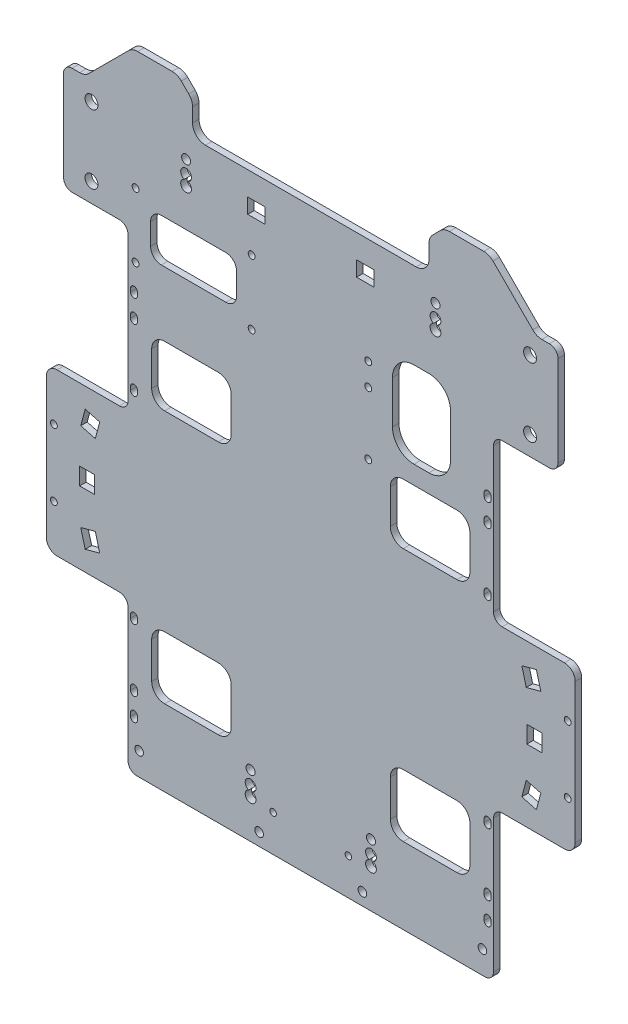
SolidWorks part; units mm, degrees
ref_plane "前视基准面" through (0, 0, 0) normal (0, 0, 1) x (1, 0, 0)
ref_plane "上视基准面" through (0, 0, 0) normal (0, 1, 0) x (1, 0, 0)
ref_plane "右视基准面" through (0, 0, 0) normal (1, 0, 0) x (0, 0, -1)
sketch "草图1" plane through (0, 0, 0) normal (0, 0, 1) x (1, 0, 0)
  line L0 (-31.6443, 41.9463) -> (-31.6443, -8.1198) construction
  line L1 (-146.6443, 41.9463) -> (83.3557, 41.9463)
  line L2 (-146.6443, 41.9463) -> (-146.6443, -8.0537)
  line L3 (-116.6443, -228.0537) -> (53.3557, -228.0537)
  line L4 (83.3557, 41.9463) -> (83.3557, -8.0537)
  line L5 (83.3557, -8.0537) -> (53.3557, -8.0537)
  line L6 (33.3557, 1.9463) -> (6.3557, 1.9463)
  line L7 (83.3557, -83.0537) -> (53.3557, -83.0537)
  line L8 (53.3557, -8.0537) -> (53.3557, -83.0537)
  line L9 (83.3557, -158.0537) -> (53.3557, -158.0537)
  line L10 (33.3557, -38.0537) -> (6.3557, -38.0537)
  line L11 (6.3557, 1.9463) -> (6.3557, -38.0537)
  line L12 (53.3557, -158.0537) -> (53.3557, -228.0537)
  line L14 (-116.6443, -158.0537) -> (-116.6443, -228.0537)
  line L15 (-146.6443, -158.0537) -> (-116.6443, -158.0537)
  line L16 (-146.6443, -83.0537) -> (-116.6443, -83.0537)
  line L17 (-116.6443, -8.0537) -> (-116.6443, -83.0537)
  line L18 (-146.6443, -8.0537) -> (-116.6443, -8.0537)
  line L19 (-146.6443, -83.0537) -> (-146.6443, -158.0537)
  line L20 (33.3557, 1.9463) -> (33.3557, -38.0537)
  line L22 (83.3557, -83.0537) -> (83.3557, -158.0537)
  circle A0 centre (-4.8943, -7.2137) radius 1.6
  circle A1 centre (-4.8943, -17.7137) radius 1.6
  circle A2 centre (-4.8943, -46.7137) radius 1.6
  dimension "D10" = 3.2
  dimension "D12" = 49.16
  dimension "D13" = 10.5
  dimension "D14" = 29
  dimension "D15" = 3.2
  dimension "D16" = 3.2
  dimension "D1" = 230
  dimension "D2" = 50
  dimension "D3" = 50
  dimension "D4" = 30
  dimension "D5" = 30
  dimension "D6" = 75
  dimension "D7" = 70
  dimension "D8" = 75
  dimension "D9" = 27
  dimension "D11" = 11.25
extrude "凸台-拉伸1" add sketch "草图1" along normal blind 3
sketch "草图2" plane through (0, 0, 3) normal (0, 0, 1) x (1, 0, 0)
  line L0 (83.3557, -158.0537) -> (83.3557, -83.0537) construction
  line L1 (-116.6443, -228.0537) -> (53.3557, -228.0537) construction
  circle A0 centre (25.3557, -107.0537) radius 6
  circle A1 centre (31.8472, -88.1365) radius 6
  circle A2 centre (25.3557, -68.1365) radius 6
  dimension "D4" = 12
  dimension "D5" = 12
  dimension "D6" = 12
  dimension "D1" = 58
  dimension "D2" = 121
  dimension "D3" = 20
  dimension "D7" = 20
sketch "草图3" plane through (0, 0, 3) normal (0, 0, 1) x (1, 0, 0)
  line L0 (49.0057, -72.5537) -> (49.0057, -74.1537)
  line L1 (53.3557, -228.0537) -> (53.3557, -158.0537) construction
  line L2 (52.2057, -72.5537) -> (52.2057, -74.1537)
  line L3 (53.3557, -83.0537) -> (53.3557, -8.0537) construction
  line L4 (-31.6443, -208.0537) -> (-31.6443, 49791.9463) construction
  line L5 (-116.6443, -228.0537) -> (53.3557, -228.0537) construction
  line L6 (83.3557, 41.9463) -> (-146.6443, 41.9463) construction
  line L7 (49.0057, -43.5537) -> (49.0057, -45.1537)
  line L8 (52.2057, -43.5537) -> (52.2057, -45.1537)
  line L9 (49.0057, -33.0537) -> (49.0057, -34.6537)
  line L10 (52.2057, -33.0537) -> (52.2057, -34.6537)
  line L11 (49.0057, -164.4537) -> (49.0057, -166.0537)
  line L12 (52.2057, -164.4537) -> (52.2057, -166.0537)
  line L13 (49.0057, -193.4537) -> (49.0057, -195.0537)
  line L14 (52.2057, -193.4537) -> (52.2057, -195.0537)
  line L15 (49.0057, -203.9537) -> (49.0057, -205.5537)
  line L16 (52.2057, -203.9537) -> (52.2057, -205.5537)
  line L17 (-115.4943, -33.0537) -> (-115.4943, -34.6537)
  line L18 (-112.2943, -33.0537) -> (-112.2943, -34.6537)
  line L19 (-115.4943, -43.5537) -> (-115.4943, -45.1537)
  line L20 (-112.2943, -43.5537) -> (-112.2943, -45.1537)
  line L21 (-115.4943, -72.5537) -> (-115.4943, -74.1537)
  line L22 (-112.2943, -72.5537) -> (-112.2943, -74.1537)
  line L23 (-115.4943, -164.4537) -> (-115.4943, -166.0537)
  line L24 (-112.2943, -164.4537) -> (-112.2943, -166.0537)
  line L25 (-115.4943, -193.4537) -> (-115.4943, -195.0537)
  line L26 (-112.2943, -193.4537) -> (-112.2943, -195.0537)
  line L27 (-115.4943, -203.9537) -> (-115.4943, -205.5537)
  line L28 (-112.2943, -203.9537) -> (-112.2943, -205.5537)
  arc A0 (49.0057, -166.0537) -> (52.2057, -166.0537) centre (50.6057, -166.0537) ccw
  arc A1 (49.0057, -195.0537) -> (52.2057, -195.0537) centre (50.6057, -195.0537) ccw
  arc A2 (49.0057, -205.5537) -> (52.2057, -205.5537) centre (50.6057, -205.5537) ccw
  arc A3 (52.2057, -72.5537) -> (49.0057, -72.5537) centre (50.6057, -72.5537) ccw
  arc A4 (52.2057, -43.5537) -> (49.0057, -43.5537) centre (50.6057, -43.5537) ccw
  arc A5 (52.2057, -33.0537) -> (49.0057, -33.0537) centre (50.6057, -33.0537) ccw
  arc A12 (49.0057, -34.6537) -> (52.2057, -34.6537) centre (50.6057, -34.6537) ccw
  arc A13 (49.0057, -45.1537) -> (52.2057, -45.1537) centre (50.6057, -45.1537) ccw
  arc A14 (49.0057, -74.1537) -> (52.2057, -74.1537) centre (50.6057, -74.1537) ccw
  arc A15 (52.2057, -203.9537) -> (49.0057, -203.9537) centre (50.6057, -203.9537) ccw
  arc A16 (52.2057, -193.4537) -> (49.0057, -193.4537) centre (50.6057, -193.4537) ccw
  arc A17 (52.2057, -164.4537) -> (49.0057, -164.4537) centre (50.6057, -164.4537) ccw
  arc A18 (-115.4943, -33.0537) -> (-112.2943, -33.0537) centre (-113.8943, -33.0537) cw
  arc A19 (-112.2943, -34.6537) -> (-115.4943, -34.6537) centre (-113.8943, -34.6537) cw
  arc A20 (-115.4943, -43.5537) -> (-112.2943, -43.5537) centre (-113.8943, -43.5537) cw
  arc A21 (-112.2943, -45.1537) -> (-115.4943, -45.1537) centre (-113.8943, -45.1537) cw
  arc A22 (-115.4943, -72.5537) -> (-112.2943, -72.5537) centre (-113.8943, -72.5537) cw
  arc A23 (-112.2943, -74.1537) -> (-115.4943, -74.1537) centre (-113.8943, -74.1537) cw
  arc A24 (-115.4943, -164.4537) -> (-112.2943, -164.4537) centre (-113.8943, -164.4537) cw
  arc A25 (-112.2943, -166.0537) -> (-115.4943, -166.0537) centre (-113.8943, -166.0537) cw
  arc A26 (-115.4943, -193.4537) -> (-112.2943, -193.4537) centre (-113.8943, -193.4537) cw
  arc A27 (-112.2943, -195.0537) -> (-115.4943, -195.0537) centre (-113.8943, -195.0537) cw
  arc A28 (-115.4943, -203.9537) -> (-112.2943, -203.9537) centre (-113.8943, -203.9537) cw
  arc A29 (-112.2943, -205.5537) -> (-115.4943, -205.5537) centre (-113.8943, -205.5537) cw
  point P24 (-31.6443, -228.0537)
  dimension "D1" = 3.2
  dimension "D2" = 3.2
  dimension "D3" = 3.2
  dimension "D10" = 3.2
  dimension "D11" = 3.2
  dimension "D12" = 3.2
  dimension "D4" = 29
  dimension "D5" = 22.5
  dimension "D6" = 2.75
  dimension "D7" = 0
  dimension "D8" = 2.75
  dimension "D9" = 10.5
  dimension "D13" = 2.75
  dimension "D14" = 2.75
  dimension "D15" = 29
  dimension "D16" = 10.5
  dimension "D17" = 75
  dimension "D18" = 2.75
extrude "切除-拉伸1" cut sketch "草图3" against normal blind 10
fillet "圆角1" radius 4 10 edges at (83.3557, 41.9463, 1.5) (83.3557, -8.0537, 1.5) (83.3557, -83.0537, 1.5) (83.3557, -158.0537, 1.5) (53.3557, -228.0537, 1.5) (-116.6443, -228.0537, 1.5) (-146.6443, -158.0537, 1.5) (-146.6443, -83.0537, 1.5) (-146.6443, -8.0537, 1.5) (-146.6443, 41.9463, 1.5)
sketch "草图4" plane through (0, 0, 3) normal (0, 0, 1) x (1, 0, 0)
  line L0 (83.3557, -120.5537) -> (-182.0134, -120.5537) construction
  line L1 (83.3557, -154.0537) -> (83.3557, -87.0537) construction
  line L2 (-31.6443, -228.0537) -> (-31.6443, 167.0976) construction
  line L3 (-112.6443, -228.0537) -> (49.3557, -228.0537) construction
  line L4 (75.8557, -116.5537) -> (75.8557, -124.5537)
  line L5 (75.8557, -124.5537) -> (68.8557, -124.5537)
  line L6 (68.8557, -124.5537) -> (68.8557, -116.5537)
  line L7 (68.8557, -116.5537) -> (75.8557, -116.5537)
  line L8 (75.3557, -100.0537) -> (73.2852, -92.3263)
  line L9 (73.2852, -92.3263) -> (66.5237, -94.138)
  line L10 (66.5237, -94.138) -> (68.5942, -101.8654)
  line L11 (68.5942, -101.8654) -> (75.3557, -100.0537)
  line L13 (79.3557, -83.0537) -> (53.3557, -83.0537) construction
  line L14 (66.5237, -146.9694) -> (68.5942, -139.242)
  line L15 (73.2852, -148.7811) -> (66.5237, -146.9694)
  line L16 (75.3557, -141.0537) -> (73.2852, -148.7811)
  line L17 (68.5942, -139.242) -> (75.3557, -141.0537)
  line L18 (-129.8123, -94.138) -> (-131.8828, -101.8654)
  line L19 (-136.5737, -92.3263) -> (-129.8123, -94.138)
  line L20 (-138.6443, -100.0537) -> (-136.5737, -92.3263)
  line L21 (-131.8828, -101.8654) -> (-138.6443, -100.0537)
  line L22 (-132.1443, -124.5537) -> (-132.1443, -116.5537)
  line L23 (-139.1443, -124.5537) -> (-132.1443, -124.5537)
  line L24 (-139.1443, -116.5537) -> (-139.1443, -124.5537)
  line L25 (-132.1443, -116.5537) -> (-139.1443, -116.5537)
  line L26 (-136.5737, -148.7811) -> (-129.8123, -146.9694)
  line L27 (-138.6443, -141.0537) -> (-136.5737, -148.7811)
  line L28 (-131.8828, -139.242) -> (-138.6443, -141.0537)
  line L29 (-129.8123, -146.9694) -> (-131.8828, -139.242)
  dimension "D1" = 4
  dimension "D2" = 8
  dimension "D3" = 7
  dimension "D4" = 14.5
  dimension "D5" = 8
  dimension "D6" = 7
  dimension "D8" = 17
  dimension "D9" = 8
  dimension "D10" = 8
extrude "切除-拉伸2" cut sketch "草图4" against normal through all
sketch "草图5" plane through (0, 0, 3) normal (0, 0, 1) x (1, 0, 0)
  line L0 (-31.6443, -291.5199) -> (-31.6443, 100.9656) construction
  line L6 (83.3557, -4.0537) -> (83.3557, 37.9463) construction
  line L7 (79.3557, 41.9463) -> (-142.6443, 41.9463) construction
  circle A0 centre (70.3557, 32.9463) radius 3
  circle A1 centre (70.3557, 0.9463) radius 3
  circle A2 centre (-133.6443, 0.9463) radius 3
  circle A3 centre (-133.6443, 32.9463) radius 3
  dimension "D8" = 6
  dimension "D9" = 6
  dimension "D10" = 9
  dimension "D11" = 13
  dimension "D12" = 13
  dimension "D13" = 32
extrude "切除-拉伸3" cut sketch "草图5" against normal through all
sketch "草图6" plane through (0, 0, 3) normal (0, 0, 1) x (1, 0, 0)
  line L1 (-116.6443, -8.0537) -> (-116.6443, -83.0537) construction
  line L2 (79.3557, 41.9463) -> (-142.6443, 41.9463) construction
  line L3 (-106.1443, -1.5537) -> (-106.1443, -11.5537)
  line L4 (-101.1443, -16.5537) -> (-71.1443, -16.5537)
  line L5 (-66.1443, -11.5537) -> (-66.1443, -1.5537)
  line L6 (-71.1443, 3.4463) -> (-101.1443, 3.4463)
  circle A2 centre (-113.1443, -21.5537) radius 1.6
  circle A3 centre (-59.1443, -21.5537) radius 1.6
  circle A4 centre (-113.1443, 8.4463) radius 1.6
  circle A5 centre (-59.1443, 8.4463) radius 1.6
  arc A6 (-106.1443, -1.5537) -> (-101.1443, 3.4463) centre (-101.1443, -1.5537) cw
  arc A7 (-71.1443, 3.4463) -> (-66.1443, -1.5537) centre (-71.1443, -1.5537) cw
  arc A8 (-71.1443, -16.5537) -> (-66.1443, -11.5537) centre (-71.1443, -11.5537) ccw
  arc A9 (-101.1443, -16.5537) -> (-106.1443, -11.5537) centre (-101.1443, -11.5537) cw
  dimension "D1" = 33.5
  dimension "D3" = 3.5
  dimension "D5" = 3.2
  dimension "D7" = 3.2
  dimension "D8" = 3.2
  dimension "D9" = 3.2
  dimension "D15" = 5
  dimension "D2" = 33.5
  dimension "D4" = 3.5
  dimension "D6" = 54
  dimension "D10" = 5
  dimension "D11" = 5
  dimension "D12" = 7
  dimension "D13" = 7
  dimension "D14" = 54
extrude "切除-拉伸4" cut sketch "草图6" against normal through all
sketch "草图9" plane through (0, 0, 3) normal (0, 0, 1) x (1, 0, 0)
  circle A0 centre (48.1967, -217.4028) radius 2
  circle A1 centre (-7.6162, -222.2619) radius 2
  circle A2 centre (-55.6724, -222.2619) radius 2
  circle A3 centre (-111.4853, -217.4028) radius 2
extrude "切除-拉伸6" cut sketch "草图9" against normal blind 10
sketch "草图10" plane through (0, 0, 3) normal (0, 0, 1) x (1, 0, 0)
  line L0 (53.3557, 23.9463) -> (67.1227, 23.9463) construction
  line L5 (-2.3201, 30.9463) -> (-2.3201, 23.9463)
  line L6 (-2.3201, 23.9463) -> (-10.3201, 23.9463)
  line L7 (-10.3201, 23.9463) -> (-10.3201, 30.9463)
  line L8 (-10.3201, 30.9463) -> (-2.3201, 30.9463)
  line L10 (79.3557, 41.9463) -> (-142.6443, 41.9463) construction
  line L11 (-31.6443, 41.9463) -> (-31.6443, 68.0542) construction
  line L17 (-52.9685, 30.9463) -> (-60.9685, 30.9463)
  line L18 (-52.9685, 23.9463) -> (-52.9685, 30.9463)
  line L19 (-60.9685, 23.9463) -> (-52.9685, 23.9463)
  line L20 (-60.9685, 30.9463) -> (-60.9685, 23.9463)
  circle A0 centre (-14.1443, -211.0537) radius 1.5
  circle A1 centre (-49.1443, -211.0537) radius 1.5
extrude "切除-拉伸7" cut sketch "草图10" against normal blind 10
fillet "圆角2" radius 10 4 edges at (33.3557, -38.0537, 1.5) (6.3557, -38.0537, 1.5) (6.3557, 1.9463, 1.5) (33.3557, 1.9463, 1.5)
fillet "圆角3" radius 4 6 edges at (53.3557, -158.0537, 1.5) (-116.6443, -158.0537, 1.5) (-116.6443, -83.0537, 1.5) (-116.6443, -8.0537, 1.5) (53.3557, -83.0537, 1.5) (53.3557, -8.0537, 1.5)
sketch "草图12" plane through (0, 0, 3) normal (0, 0, 1) x (1, 0, 0)
  line L0 (-105.6443, -52.5537) -> (-105.6443, -68.5537)
  line L1 (-99.6443, -74.5537) -> (-74.6443, -74.5537)
  line L2 (-68.6443, -68.5537) -> (-68.6443, -52.5537)
  line L3 (-74.6443, -46.5537) -> (-99.6443, -46.5537)
  line L4 (-116.6443, -12.0537) -> (-116.6443, -79.0537) construction
  line L5 (79.3557, 41.9463) -> (-142.6443, 41.9463) construction
  line L6 (-105.6443, -169.5537) -> (-105.6443, -186.5537)
  line L7 (-99.6443, -192.5537) -> (-74.6443, -192.5537)
  line L8 (-68.6443, -186.5537) -> (-68.6443, -169.5537)
  line L9 (-74.6443, -163.5537) -> (-99.6443, -163.5537)
  line L10 (-112.6443, -228.0537) -> (49.3557, -228.0537) construction
  line L11 (-31.6443, 41.9463) -> (-31.6443, 54.5783) construction
  line L12 (79.3557, 41.9463) -> (-142.6443, 41.9463) construction
  line L13 (5.3557, -186.5537) -> (5.3557, -169.5537)
  line L14 (36.3557, -192.5537) -> (11.3557, -192.5537)
  line L15 (42.3557, -169.5537) -> (42.3557, -186.5537)
  line L16 (11.3557, -163.5537) -> (36.3557, -163.5537)
  line L17 (5.3557, -68.5537) -> (5.3557, -52.5537)
  line L18 (36.3557, -74.5537) -> (11.3557, -74.5537)
  line L19 (42.3557, -52.5537) -> (42.3557, -68.5537)
  line L20 (11.3557, -46.5537) -> (36.3557, -46.5537)
  arc A0 (-68.6443, -52.5537) -> (-74.6443, -46.5537) centre (-74.6443, -52.5537) ccw
  arc A1 (-74.6443, -74.5537) -> (-68.6443, -68.5537) centre (-74.6443, -68.5537) ccw
  arc A2 (-99.6443, -74.5537) -> (-105.6443, -68.5537) centre (-99.6443, -68.5537) cw
  arc A3 (-105.6443, -52.5537) -> (-99.6443, -46.5537) centre (-99.6443, -52.5537) cw
  arc A4 (-68.6443, -186.5537) -> (-74.6443, -192.5537) centre (-74.6443, -186.5537) cw
  arc A5 (-74.6443, -163.5537) -> (-68.6443, -169.5537) centre (-74.6443, -169.5537) cw
  arc A6 (-99.6443, -192.5537) -> (-105.6443, -186.5537) centre (-99.6443, -186.5537) cw
  arc A7 (-105.6443, -169.5537) -> (-99.6443, -163.5537) centre (-99.6443, -169.5537) cw
  arc A8 (5.3557, -186.5537) -> (11.3557, -192.5537) centre (11.3557, -186.5537) ccw
  arc A9 (36.3557, -192.5537) -> (42.3557, -186.5537) centre (36.3557, -186.5537) ccw
  arc A10 (11.3557, -163.5537) -> (5.3557, -169.5537) centre (11.3557, -169.5537) ccw
  arc A11 (42.3557, -169.5537) -> (36.3557, -163.5537) centre (36.3557, -169.5537) ccw
  arc A12 (11.3557, -74.5537) -> (5.3557, -68.5537) centre (11.3557, -68.5537) cw
  arc A13 (36.3557, -74.5537) -> (42.3557, -68.5537) centre (36.3557, -68.5537) ccw
  arc A14 (5.3557, -52.5537) -> (11.3557, -46.5537) centre (11.3557, -52.5537) cw
  arc A15 (42.3557, -52.5537) -> (36.3557, -46.5537) centre (36.3557, -52.5537) ccw
  dimension "D5" = 6
  dimension "D8" = 6
  dimension "D1" = 11
  dimension "D2" = 48
  dimension "D3" = 88.5
  dimension "D4" = 116.5
  dimension "D6" = 35.5
  dimension "D7" = 64.5
extrude "切除-拉伸8" cut sketch "草图12" against normal through all
sketch "草图13" plane through (0, 0, 0) normal (0, 0, 1) x (1, 0, 0)
  line L0 (79.3557, 41.9463) -> (-142.6443, 41.9463) construction
  line L3 (51.3557, 63.9463) -> (30.3557, 63.9463)
  line L4 (23.3557, 56.9463) -> (23.3557, 41.9463)
  line L5 (83.3557, -4.0537) -> (83.3557, 37.9463) construction
  line L6 (73.3557, 41.9463) -> (51.3557, 63.9463)
  line L7 (30.3557, 63.9463) -> (23.3557, 56.9463)
  line L9 (-31.6443, 41.9463) -> (-31.6443, 51.7883) construction
  line L10 (-93.6443, 63.9463) -> (-86.6443, 56.9463)
  line L11 (-114.6443, 63.9463) -> (-93.6443, 63.9463)
  line L12 (-136.6443, 41.9463) -> (-114.6443, 63.9463)
  line L13 (-136.6443, 41.9463) -> (-86.6443, 41.9463)
  line L14 (-86.6443, 56.9463) -> (-86.6443, 41.9463)
  line L15 (23.3557, 41.9463) -> (73.3557, 41.9463)
  dimension "D1" = 22
  dimension "D2" = 135
  dimension "D3" = 60
  dimension "D4" = 15
  dimension "D5" = 21
extrude "凸台-拉伸2" add sketch "草图13" along normal up to surface (3 mm away) up to face at (23.8557, -60.5537, 3)
fillet "圆角4" radius 6 10 edges at (23.3557, 41.9463, 1.5) (23.3557, 56.9463, 1.5) (30.3557, 63.9463, 1.5) (51.3557, 63.9463, 1.5) (73.3557, 41.9463, 1.5) (-136.6443, 41.9463, 1.5) (-114.6443, 63.9463, 1.5) (-93.6443, 63.9463, 1.5) (-86.6443, 56.9463, 1.5) (-86.6443, 41.9463, 1.5)
sketch "草图14" plane through (0, 0, 0) normal (0, 0, 1) x (1, 0, 0)
  line L0 (-142.6443, -83.0537) -> (-149.6443, -83.0537)
  line L1 (-154.6443, -88.0537) -> (-154.6443, -153.0537)
  line L2 (-149.6443, -158.0537) -> (-142.6443, -158.0537)
  line L3 (-146.6443, -87.0537) -> (-146.6443, -154.0537) construction
  line L4 (-146.6443, -87.0537) -> (-146.6443, -154.0537)
  line L5 (-31.6443, 41.9463) -> (-31.6443, 68.3446) construction
  line L6 (17.3557, 41.9463) -> (-80.6443, 41.9463) construction
  line L7 (83.3557, -87.0537) -> (83.3557, -154.0537)
  line L8 (86.3557, -158.0537) -> (79.3557, -158.0537)
  line L9 (91.3557, -88.0537) -> (91.3557, -153.0537)
  line L10 (79.3557, -83.0537) -> (86.3557, -83.0537)
  arc A0 (-154.6443, -153.0537) -> (-149.6443, -158.0537) centre (-149.6443, -153.0537) ccw
  arc A1 (-154.6443, -88.0537) -> (-149.6443, -83.0537) centre (-149.6443, -88.0537) cw
  arc A2 (-146.6443, -154.0537) -> (-142.6443, -158.0537) centre (-142.6443, -154.0537) ccw construction
  arc A3 (-142.6443, -83.0537) -> (-146.6443, -87.0537) centre (-142.6443, -87.0537) ccw construction
  arc A4 (-146.6443, -154.0537) -> (-142.6443, -158.0537) centre (-142.6443, -154.0537) ccw
  arc A5 (-142.6443, -83.0537) -> (-146.6443, -87.0537) centre (-142.6443, -87.0537) ccw
  arc A6 (79.3557, -83.0537) -> (83.3557, -87.0537) centre (79.3557, -87.0537) cw
  arc A7 (83.3557, -154.0537) -> (79.3557, -158.0537) centre (79.3557, -154.0537) cw
  arc A8 (91.3557, -153.0537) -> (86.3557, -158.0537) centre (86.3557, -153.0537) cw
  arc A9 (91.3557, -88.0537) -> (86.3557, -83.0537) centre (86.3557, -88.0537) ccw
  dimension "D1" = 5
  dimension "D2" = 8
extrude "凸台-拉伸3" add sketch "草图14" along normal up to surface (3 mm away) up to face at (23.8557, -60.5537, 3)
sketch "草图16" plane through (0, 0, 0) normal (0, 0, 1) x (1, 0, 0)
  line L0 (91.3557, -153.0537) -> (91.3557, -88.0537) construction
  line L2 (86.3557, -83.0537) -> (57.3557, -83.0537) construction
  line L3 (57.3557, -158.0537) -> (86.3557, -158.0537) construction
  line L4 (-31.6443, 41.9463) -> (-31.6443, 65.2541) construction
  line L5 (17.3557, 41.9463) -> (-80.6443, 41.9463) construction
  circle A0 centre (87.8557, -105.7137) radius 1.6
  circle A1 centre (87.8557, -136.7437) radius 1.6
  circle A2 centre (-151.1443, -105.7137) radius 1.6
  circle A3 centre (-151.1443, -136.7437) radius 1.6
  dimension "D1" = 3.2
  dimension "D4" = 21.31
  dimension "D2" = 3.5
  dimension "D3" = 22.66
extrude "切除-拉伸10" cut sketch "草图16" along normal through all
sketch "草图17" plane through (0, 0, 3) normal (0, 0, 1) x (1, 0, 0)
  line L0 (17.3557, 41.9463) -> (-80.6443, 41.9463) construction
  line L1 (-146.6443, 37.9463) -> (-146.6443, -4.0537) construction
  line L2 (-31.6443, 41.9463) -> (-31.6443, 54.4059) construction
  line L3 (-116.6443, -162.0537) -> (-116.6443, -224.0537) construction
  line L4 (-112.6443, -228.0537) -> (49.3557, -228.0537) construction
  circle A0 centre (-89.6443, 31.7963) radius 2.1
  arc A1 (-88.7914, 23.2963) -> (-90.4972, 23.2963) centre (-89.6443, 25.6463) ccw
  arc A2 (-90.4972, 23.2963) -> (-88.7914, 23.2963) centre (-89.6443, 20.9463) ccw
  circle A3 centre (-59.6443, -199.2037) radius 2.1
  arc A5 (-58.7914, -207.7037) -> (-60.4972, -207.7037) centre (-59.6443, -205.3537) ccw
  arc A6 (-60.4972, -207.7037) -> (-58.7914, -207.7037) centre (-59.6443, -210.0537) ccw
  circle A7 centre (-3.6443, -199.2037) radius 2.1
  arc A8 (-2.7914, -207.7037) -> (-4.4972, -207.7037) centre (-3.6443, -210.0537) cw
  arc A9 (-4.4972, -207.7037) -> (-2.7914, -207.7037) centre (-3.6443, -205.3537) cw
  circle A10 centre (26.3557, 31.7963) radius 2.1
  arc A11 (27.2086, 23.2963) -> (25.5028, 23.2963) centre (26.3557, 20.9463) cw
  arc A12 (25.5028, 23.2963) -> (27.2086, 23.2963) centre (26.3557, 25.6463) cw
  dimension "D1" = 10.15
  dimension "D2" = 4.2
  dimension "D4" = 5
  dimension "D6" = 4.7
  dimension "D7" = 4.2
  dimension "D10" = 6.15
  dimension "D11" = 5
  dimension "D12" = 5
  dimension "D3" = 57
  dimension "D5" = 6.15
  dimension "D8" = 57
  dimension "D9" = 28.85
  dimension "D13" = 4.7
  dimension "D14" = 57
extrude "切除-拉伸11" cut sketch "草图17" against normal through all
